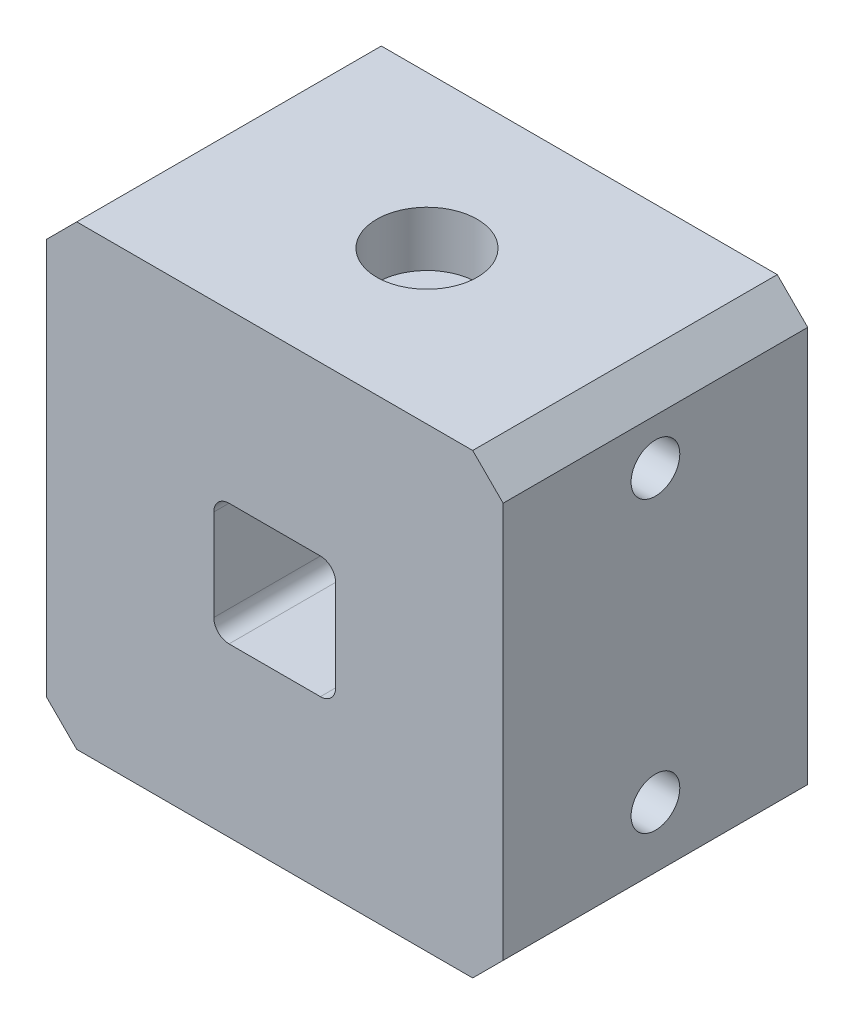
SolidWorks part; units mm, degrees
material "6061 Alloy"
ref_plane "Front Plane" through (0, 0, 0) normal (0, 0, 1) x (1, 0, 0)
ref_plane "Top Plane" through (0, 0, 0) normal (0, 1, 0) x (1, 0, 0)
ref_plane "Right Plane" through (0, 0, 0) normal (1, 0, 0) x (0, 0, -1)
sketch "Sketch1" plane through (0, 0, 0) normal (0, 0, 1) x (1, 0, 0)
  line L1 (-2, -2) -> (2, -2)
  line L2 (-2, -2) -> (-2, 2)
  line L3 (-2, 2) -> (2, 2)
  line L4 (2, -2) -> (2, 2)
  line L5 (-2, -2) -> (2, 2) construction
  line L6 (-2, 2) -> (2, -2) construction
  line L7 (-7.5, -7.5) -> (7.5, -7.5)
  line L8 (-7.5, -7.5) -> (-7.5, 7.5)
  line L9 (-7.5, 7.5) -> (7.5, 7.5)
  line L10 (7.5, -7.5) -> (7.5, 7.5)
  line L11 (-7.5, -7.5) -> (7.5, 7.5) construction
  line L12 (-7.5, 7.5) -> (7.5, -7.5) construction
  point P0 (0, 0)
  dimension "D1" = 4
  dimension "D2" = 4
  dimension "D3" = 15
  dimension "D4" = 15
extrude "Boss-Extrude1" add sketch "Sketch1" against normal blind 10
fillet "Fillet1" radius 0.5 4 edges at (2, -2, -5) (2, 2, -5) (-2, 2, -5) (-2, -2, -5)
hole_wizard "CBORE for M1.6 Hexagon socket head cap screws1" positions "Sketch2" profile "Sketch3" counterbore size "M1.6" standard "GB" end condition through all
sketch "Sketch2" plane through (0, 7.5, 0) normal (0, 1, 0) x (1, 0, 0)
  line L0 (7.5, 0) -> (-7.5, 0) construction
  point P0 (0, 5)
  dimension "D1" = 5
sketch "Sketch3" plane through (0, 7.5, -5) normal (1, 0, 0) x (0, 0, 1)
  line L0 (0, 0) -> (0, 15)
  line L1 (0, 15) -> (0.9, 15)
  line L3 (0.9, 15) -> (0.9, 1.8)
  line L4 (0.9, 1.8) -> (1.65, 1.8)
  line L5 (1.65, 1.8) -> (1.65, 0)
  line L7 (1.65, 0) -> (0, 0)
  line L11 (0, -6.35) -> (0, 107.95) construction
  dimension "Thru Hole Dia." = 1.8
  dimension "Thru Hole Depth" = 15
  dimension "C'Bore Dia." = 3.3
  dimension "C'Bore Depth" = 1.8
hole_wizard "M2 Tapped Hole1" positions "Sketch4" profile "Sketch6" tap size "M2" standard "GB"
sketch "Sketch4" plane through (-7.5, 0, 0) normal (-1, 0, 0) x (0, 0, 1)
  line L0 (-5, 5) -> (-5, -4.5) construction
  line L1 (0, 7.5) -> (0, -7.5) construction
  point P0 (-5, 5)
  point P2 (-5, -4.5)
  dimension "D1" = 5
  dimension "D2" = 4.5
  dimension "D3" = 5
cosmetic thread "Hole Thread1" parameters "D1"=4.6, "D2"=2
cosmetic thread "Hole Thread2" parameters "D1"=4.6, "D2"=2
sketch "Sketch6" plane through (-7.5, 5, -5) normal (0, 1, 0) x (0, 0, 1)
  line L0 (0, 0) -> (0, 5.4807)
  line L1 (0, 5.4807) -> (0.8, 5)
  line L2 (0.8, 5) -> (0.8, 0)
  line L5 (0.8, 0) -> (0, 0)
  line L10 (0, 5.4807) -> (-0.8, 5) construction
  line L11 (0, -6.35) -> (0, 107.95) construction
  dimension "Tap Drill Dia." = 1.6
  dimension "Tap Drill Depth" = 5
  dimension "Drill Angle" = 118
mirror "Mirror1" about plane through (0, 0, 0) normal (1, 0, 0) of "M2 Tapped Hole1"
cosmetic thread "Hole Thread3" parameters "D1"=4.6, "D2"=2
cosmetic thread "Hole Thread4" parameters "D1"=4.6, "D2"=2
chamfer "Chamfer1" distance 1 angle 45 2 edges at (7.5, -7.5, -5) (-7.5, -7.5, -5)
sketch "Sketch8" plane through (0, 0, -10) normal (0, 0, -1) x (-1, 0, 0)
  line L0 (-3.8891, 3.8891) -> (0, 0) construction
  line L1 (5.5, 0) -> (-5.5, 0) construction
  line L2 (0, 5.5) -> (0, -5.5) construction
  arc A0 (-4, 3.7749) -> (-3.7749, 4) centre (0, 0) cw construction
  arc A1 (-5.4908, 5.8182) -> (-5.8182, 5.4908) centre (0, 0) ccw
  arc A2 (-2.059, 2.1818) -> (-2.1818, 2.059) centre (0, 0) ccw
  arc A3 (-2.059, 2.1818) -> (-5.4908, 5.8182) centre (-3.7749, 4) ccw
  arc A4 (-5.8182, 5.4908) -> (-2.1818, 2.059) centre (-4, 3.7749) ccw
  arc A5 (-4, -3.7749) -> (-3.7749, -4) centre (0, 0) ccw construction
  arc A6 (-5.4908, -5.8182) -> (-5.8182, -5.4908) centre (0, 0) cw
  arc A7 (-2.059, -2.1818) -> (-2.1818, -2.059) centre (0, 0) cw
  arc A8 (-2.059, -2.1818) -> (-5.4908, -5.8182) centre (-3.7749, -4) cw
  arc A9 (-5.8182, -5.4908) -> (-2.1818, -2.059) centre (-4, -3.7749) cw
  arc A10 (4, 3.7749) -> (3.7749, 4) centre (0, 0) ccw construction
  arc A11 (5.4908, 5.8182) -> (5.8182, 5.4908) centre (0, 0) cw
  arc A12 (2.059, 2.1818) -> (2.1818, 2.059) centre (0, 0) cw
  arc A13 (2.059, 2.1818) -> (5.4908, 5.8182) centre (3.7749, 4) cw
  arc A14 (5.8182, 5.4908) -> (2.1818, 2.059) centre (4, 3.7749) cw
  arc A15 (4, -3.7749) -> (3.7749, -4) centre (0, 0) cw construction
  arc A16 (5.4908, -5.8182) -> (5.8182, -5.4908) centre (0, 0) ccw
  arc A17 (2.059, -2.1818) -> (2.1818, -2.059) centre (0, 0) ccw
  arc A18 (2.059, -2.1818) -> (5.4908, -5.8182) centre (3.7749, -4) ccw
  arc A19 (5.8182, -5.4908) -> (2.1818, -2.059) centre (4, -3.7749) ccw
  point P3 (-3.8891, 3.8891)
  point P13 (-3.8891, -3.8891)
  point P24 (3.8891, 3.8891)
  point P31 (3.8891, -3.8891)
  dimension "D2" = 5.5
  dimension "D3" = 2.5
  dimension "D1" = 45
  dimension "D4" = 4
extrude "Cut-Extrude1" cut sketch "Sketch8" against normal blind 2
hole_wizard "M2 Tapped Hole2" positions "Sketch9" profile "Sketch10" tap size "M2" standard "GB"
sketch "Sketch9" plane through (0, 0, -10) normal (0, 0, -1) x (-1, 0, 0)
  line L0 (5.5, 0) -> (-5.5, 0) construction
  line L1 (0, 5.5) -> (0, -5.5) construction
  point P0 (-6, 0)
  point P4 (0, 6)
  point P10 (6, 0)
  point P11 (0, -6)
  dimension "D1" = 6
  dimension "D2" = 6
sketch "Sketch10" plane through (6, 0, -10) normal (1, 0, 0) x (0, 1, 0)
  line L0 (0, 0) -> (0, 2.4807)
  line L1 (0, 2.4807) -> (0.8, 2)
  line L2 (0.8, 2) -> (0.8, 0)
  line L5 (0.8, 0) -> (0, 0)
  line L10 (0, 2.4807) -> (-0.8, 2) construction
  line L11 (0, -6.35) -> (0, 107.95) construction
  dimension "Tap Drill Dia." = 1.6
  dimension "Tap Drill Depth" = 2
  dimension "Drill Angle" = 118
cosmetic thread "Hole Thread5" parameters "D1"=4.6, "D2"=2
cosmetic thread "Hole Thread6" parameters "D1"=4.6, "D2"=2
cosmetic thread "Hole Thread7" parameters "D1"=4.6, "D2"=2
cosmetic thread "Hole Thread8" parameters "D1"=4.6, "D2"=2
sketch "Sketch12" plane through (0, 0, -10) normal (0, 0, -1) x (-1, 0, 0)
  circle A0 centre (0, 0) radius 3
  arc A1 (-2.059, 2.1818) -> (-2.1818, 2.059) centre (0, 0) ccw construction
  circle A2 centre (0, 0) radius 4.5
  dimension "D1" = 9
extrude "Cut-Extrude2" cut sketch "Sketch12" against normal up to surface (2 mm away) up to face at (3.8627, 3.8627, -8)
fillet "Fillet2" radius 1 8 edges at (1.2942, 4.3099, -9) (4.3099, -1.2942, -9) (1.2942, -4.3099, -9) (-1.2942, -4.3099, -9) (-4.3099, -1.2942, -9) (-4.3099, 1.2942, -9) (-1.2942, 4.3099, -9) (4.3099, 1.2942, -9)
chamfer "Chamfer2" distance 1 angle 45 2 edges at (-7.5, 7.5, -5) (7.5, 7.5, -5)
